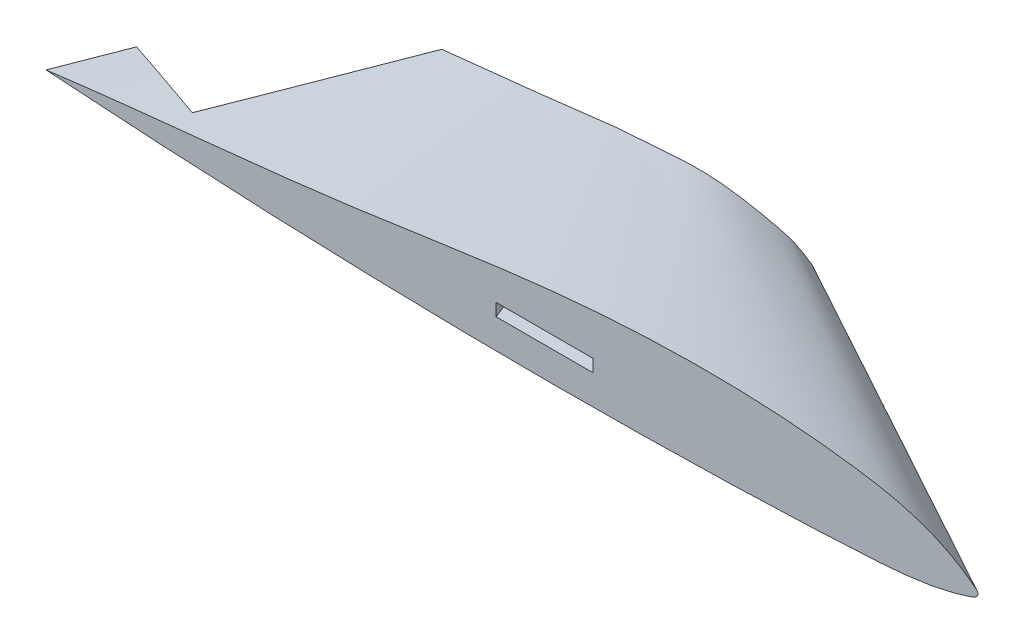
SolidWorks part; units mm, degrees
material "EPS 1.5lb"
ref_plane "Front Plane" through (0, 0, 0) normal (0, 0, 1) x (1, 0, 0)
ref_plane "Top Plane" through (0, 0, 0) normal (0, 1, 0) x (1, 0, 0)
ref_plane "Right Plane" through (0, 0, 0) normal (1, 0, 0) x (0, 0, -1)
sketch "Sketch1" plane through (0, 0, 0) normal (0, 0, 1) x (1, 0, 0)
  spline S3 degree 3 poles (-353.0971, 3.7664) (-263.6099, 15.4897) (-103.4056, 27.7025) (139.6254, 69.7319) (320.6009, 70.898) (447.0294, 49.1568) (484.462, 32.3978) (505.2254, 13.2914) knots 0 0 0 0 0.308402 0.542913 0.85017 0.887176 1 1 1 1
  spline S4 degree 3 poles (-353.0971, 3.7664) (-171.2042, -8.6227) (70.6812, -17.727) (367.6345, -8.5893) (467.935, -1.6347) (505.2254, 13.2914) knots 0 0 0 0 0.625313 0.861779 1 1 1 1
ref_plane "Plane1" through (0, 0, -180.975) normal (0, 0, 1) x (1, 0, 0)
sketch "Sketch2" plane through (0, 0, -180.975) normal (0, 0, 1) x (1, 0, 0)
  ellipse E1 centre (137.6249, -20.0426) end of major axis (189.6794, -20.0426) minor radius 48.2641 (175.2698, 13.2914) -> (153.373, 25.9598) ccw construction
  spline S0 degree 3 poles (-276.1301, 8.6931) (-231.4597, 13.8922) (-160.6069, 22.0458) (-55.2186, 32.8482) (-5.4847, 39.5878) (20.2948, 40.7341) (52.2153, 43.3112) (77.4334, 43.8548) (107.6579, 39.591) (131.1314, 34.7665) (149.4992, 30.2941) (163.4187, 23.0591) (171.5303, 16.9219) (175.2698, 13.2914) knots 0 0 0 0 0.247404 0.462109 0.504395 0.627983 0.653402 0.743134 0.818761 0.882434 0.92418 0.960505 1 1 1 1
  spline S4 degree 3 poles (-276.1301, 8.6931) (-174.261, 0.9112) (-23.6694, 0.6839) (127.5151, 0.6814) (175.2698, 13.2914) knots 0 0 0 0 0.676464 1 1 1 1
loft "Loft1" add profiles "Sketch1", "Sketch2"
fillet "Fillet1" radius 6.35 1 edges
ref_plane "Plane2" through (0, 19.812, 0) normal (0, 1, 0) x (1, 0, 0)
sketch "Sketch7" plane through (0, 19.812, 0) normal (0, 1, 0) x (1, 0, 0)
  line L0 (148.5529, 0) -> (75.4342, 180.975)
  line L1 (-13.4658, 180.975) -> (59.6529, 0)
  line L2 (59.6529, 0) -> (148.5529, 0)
  line L3 (75.4342, 180.975) -> (-13.4658, 180.975)
  line L5 (-44.6577, 180.975) -> (44.6577, 180.975) construction
  line L7 (-44.6577, 0) -> (44.6577, 0) construction
  dimension "D1" = 501.65
  dimension "D2" = 88.9
  dimension "D3" = 68
  dimension "D4" = 88.9
extrude "Cut-Extrude1" cut sketch "Sketch7" against normal mid plane 11.43
sketch "Sketch8" plane through (0, 19.812, 0) normal (0, 1, 0) x (1, 0, 0)
  line L0 (-276.1301, 180.975) -> (-353.0971, 0) construction
  line L2 (-328.3189, 58.2617) -> (-239.4979, 20.487)
  line L3 (-239.4979, 20.487) -> (-171.2438, 180.975)
  line L4 (-171.2438, 180.975) -> (-276.1301, 180.975)
  line L5 (167.9966, 180.975) -> (-276.1301, 180.975) construction
  line L6 (167.9966, 180.975) -> (-276.1301, 180.975) construction
  line L7 (-276.1301, 180.975) -> (-328.3189, 58.2617)
  dimension "D1" = 133.35
  dimension "D2" = 96.52
extrude "Cut-Extrude2" cut sketch "Sketch8" against normal through all and the other way through all
sketch "Sketch9" [suppressed] plane through (0, 0, 0) normal (0, 0, 1) x (1, 0, 0)
  line L0 (501.6041, 0) -> (501.407, 14.9983) construction
  line L1 (99.5364, 0) -> (-99.5364, 0) construction
  line L2 (501.407, 14.9983) -> (-353.0971, 3.7664) construction
  spline S0 degree 3 poles (495.958, 9.828) (496.8835, 10.1499) (497.7705, 10.5419) (499.008, 11.2994) (499.4048, 11.5805) (500.1496, 12.2315) (500.4885, 12.594) (500.9041, 13.2106) (501.0244, 13.4247) (501.2214, 13.8733) (501.2987, 14.1109) (501.3955, 14.5963) (501.415, 14.8413) (501.3938, 15.3365) (501.3526, 15.5828) (501.2176, 16.0565) (501.1224, 16.2887) (500.8939, 16.7255) (500.7606, 16.9316) (500.4639, 17.3241) (500.2996, 17.5112) (499.9516, 17.8629) (499.7676, 18.0283) (499.5755, 18.185) knots 0 0 0 0 0.25 0.25 0.375 0.375 0.5 0.5 0.5625 0.5625 0.625 0.625 0.6875 0.6875 0.75 0.75 0.8125 0.8125 0.875 0.875 0.9375 0.9375 1 1 1 1 construction
sketch "Sketch10" [suppressed] plane through (0, 0, -180.975) normal (0, 0, -1) x (-1, 0, 0)
  line L0 (-170.4193, 0) -> (-170.1582, 15.9838) construction
  line L1 (-170.1582, 15.9838) -> (276.1301, 8.6931) construction
  line L2 (99.5364, 0) -> (-99.5364, 0) construction
  spline S1 degree 3 poles (-167.9966, 19.4182) (-168.2414, 19.238) (-168.4753, 19.0462) (-168.9159, 18.6336) (-169.1233, 18.4121) (-169.4986, 17.9328) (-169.663, 17.6797) (-169.932, 17.1385) (-170.0362, 16.8477) (-170.1566, 16.2561) (-170.1738, 15.9468) (-170.1306, 15.4957) (-170.1051, 15.347) (-170.0331, 15.0527) (-169.9861, 14.9062) (-169.8194, 14.4828) (-169.6742, 14.2186) (-169.3313, 13.7181) (-169.1348, 13.4845) (-168.7149, 13.0536) (-168.4897, 12.8542) (-168.0156, 12.4801) (-167.766, 12.3054) (-167.003, 11.8211) (-166.4706, 11.5466) (-165.3734, 11.0635) (-164.8067, 10.855) (-163.6551, 10.494) (-163.0716, 10.3417) (-162.4816, 10.2129) knots 0 0 0 0 0.0625 0.0625 0.125 0.125 0.1875 0.1875 0.25 0.25 0.3125 0.3125 0.34375 0.34375 0.375 0.375 0.4375 0.4375 0.5 0.5 0.5625 0.5625 0.625 0.625 0.75 0.75 0.875 0.875 1 1 1 1 construction
ref_plane "Plane3" through (0, 14.097, 0) normal (0, 1, 0) x (1, 0, 0)
split "Split1" [suppressed] bodies to split 104
